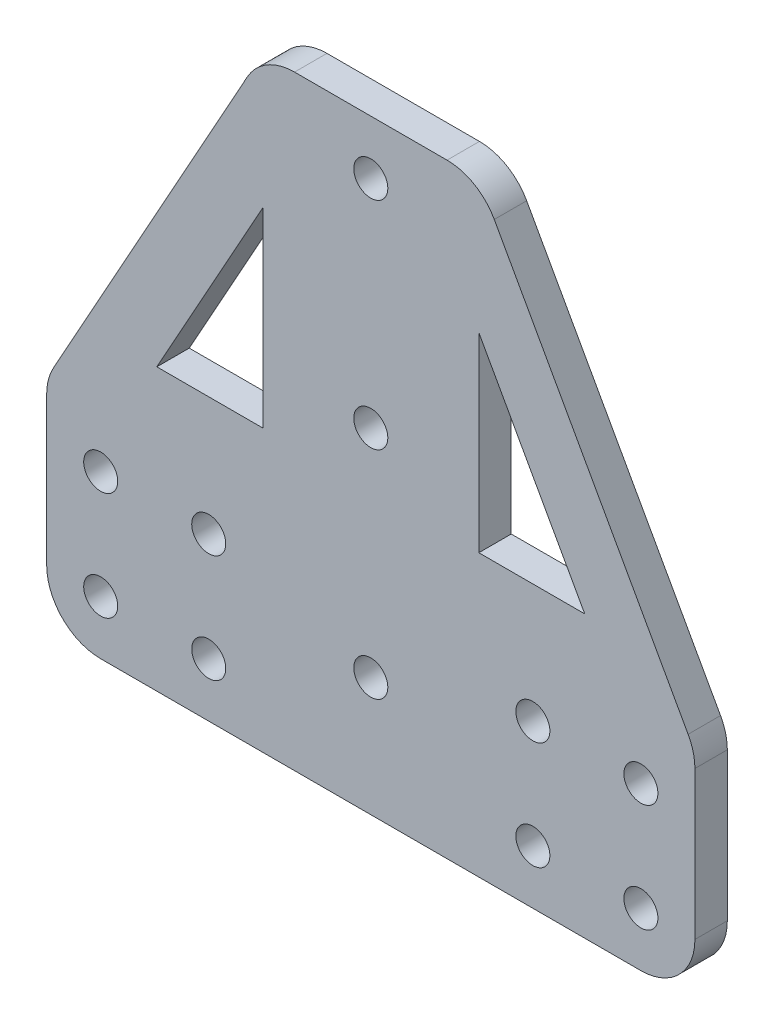
SolidWorks part; units mm, degrees
ref_plane "前视基准面" through (0, 0, 0) normal (0, 0, 1) x (1, 0, 0)
ref_plane "上视基准面" through (0, 0, 0) normal (0, 1, 0) x (1, 0, 0)
ref_plane "右视基准面" through (0, 0, 0) normal (1, 0, 0) x (0, 0, -1)
other "Configuration Table"
sketch "草图1" plane through (0, 0, 0) normal (0, 0, 1) x (1, 0, 0)
  line L0 (0, 0) -> (20, 0)
  line L1 (20, 0) -> (40, -36)
  line L2 (40, -36) -> (40, -56)
  line L3 (40, -56) -> (-20, -56)
  line L4 (-20, -56) -> (-20, -36)
  line L5 (-20, -36) -> (0, 0)
  line L6 (10, 0) -> (10, -56) construction
  dimension "D1" = 20
  dimension "D2" = 20
  dimension "D3" = 20
  dimension "D4" = 60
  dimension "D5" = 36
extrude "凸台-拉伸1" add sketch "草图1" along normal blind 3
sketch "草图2" plane through (0, 0, 3) normal (0, 0, 1) x (1, 0, 0)
  line L0 (-20, -36) -> (40, -36) construction
  line L1 (-10, -36) -> (-10, -56) construction
  line L2 (-20, -56) -> (40, -56) construction
  line L3 (-20, -46) -> (40, -46) construction
  line L4 (-20, -36) -> (-20, -56) construction
  line L5 (40, -56) -> (40, -36) construction
  line L6 (10, 0) -> (10, -56) construction
  line L7 (20, 0) -> (0, 0) construction
  line L8 (0, -12.3548) -> (-9.8029, -30)
  line L9 (-9.8029, -30) -> (0, -30)
  line L10 (0, -30) -> (0, -12.3548)
  line L12 (0, 0) -> (-20, -36) construction
  line L13 (29.8029, -30) -> (20, -30)
  line L14 (20, -30) -> (20, -12.3548)
  line L15 (20, -12.3548) -> (29.8029, -30)
  circle A0 centre (-15, -41) radius 1.575
  circle A1 centre (-5, -41) radius 1.575
  circle A2 centre (-5, -51) radius 1.575
  circle A3 centre (-15, -51) radius 1.575
  circle A4 centre (35, -51) radius 1.575
  circle A5 centre (25, -51) radius 1.575
  circle A6 centre (25, -41) radius 1.575
  circle A7 centre (35, -41) radius 1.575
  circle A8 centre (10, -25) radius 1.575
  circle A9 centre (10, -5) radius 1.575
  circle A10 centre (10, -45) radius 1.575
  point P46 (0, -11.8594)
  point P47 (0, -12.3548)
  dimension "D2" = 3.15
  dimension "D7" = 3.15
  dimension "D8" = 3.15
  dimension "D9" = 3.15
  dimension "D1" = 10
  dimension "D3" = 5
  dimension "D4" = 5
  dimension "D5" = 11
  dimension "D6" = 20
  dimension "D10" = 20
  dimension "D11" = 6
  dimension "D12" = 6
extrude "切除-拉伸1" cut sketch "草图2" against normal through all
fillet "圆角1" radius 5 6 edges at (0, 0, 1.5) (-20, -36, 1.5) (-20, -56, 1.5) (40, -56, 1.5) (40, -36, 1.5) (20, 0, 1.5)
